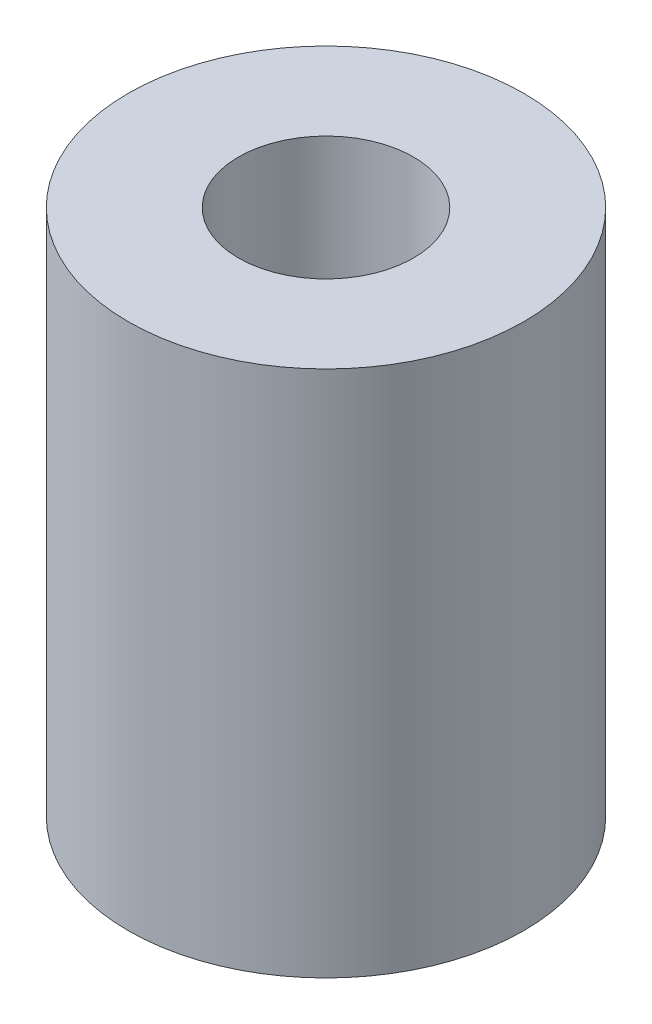
SolidWorks part; units mm, degrees
ref_plane "Front Plane" through (0, 0, 0) normal (0, 0, 1) x (1, 0, 0)
ref_plane "Top Plane" through (0, 0, 0) normal (0, 1, 0) x (1, 0, 0)
ref_plane "Right Plane" through (0, 0, 0) normal (1, 0, 0) x (0, 0, -1)
sketch "Sketch1" plane through (0, 0, 0) normal (0, 1, 0) x (1, 0, 0)
  circle A0 centre (0, 0) radius 2.1082
  circle A1 centre (0, 0) radius 4.7625
  dimension "D1" = 9.525
  dimension "D2" = 4.2164
extrude "Boss-Extrude1" add sketch "Sketch1" along normal blind 12.7
